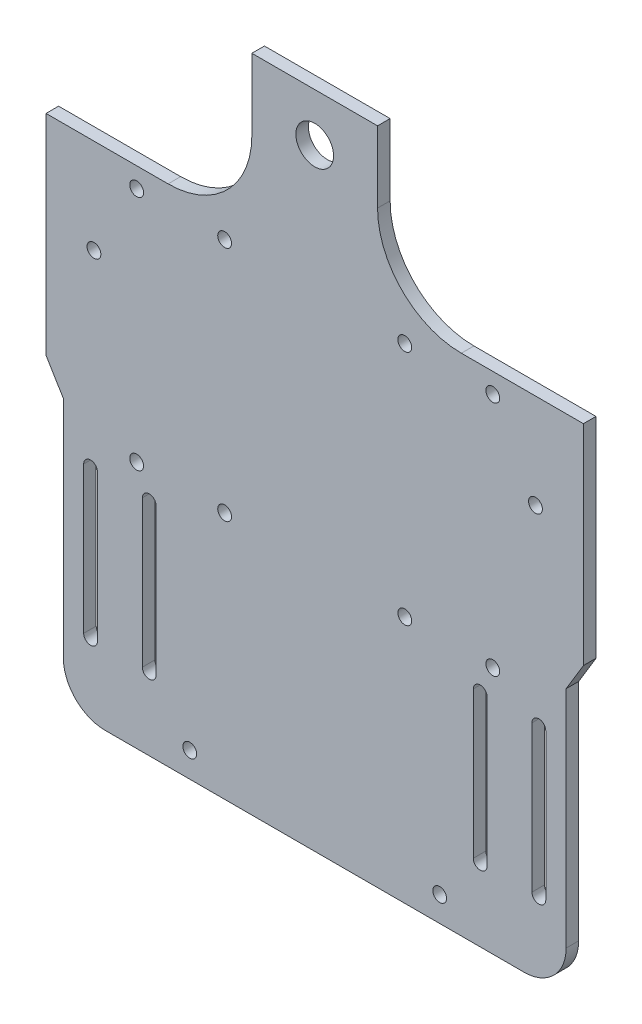
SolidWorks part; units mm, degrees
ref_plane "Front Plane" through (0, 0, 0) normal (0, 0, 1) x (1, 0, 0)
ref_plane "Top Plane" through (0, 0, 0) normal (0, 1, 0) x (1, 0, 0)
ref_plane "Right Plane" through (0, 0, 0) normal (1, 0, 0) x (0, 0, -1)
sketch "Sketch1" plane through (0, 0, 0) normal (0, 0, 1) x (1, 0, 0)
  line L0 (466.6281, 1797.6904) -> (466.6281, 1499.4405) construction
  line L7 (402.4958, 1683.2414) -> (402.4958, 1633.2414)
  line L8 (402.4958, 1633.2414) -> (406.6281, 1626.3913)
  line L14 (406.6281, 1562.7679) -> (526.6281, 1562.7679)
  line L20 (530.7604, 1633.2414) -> (526.6281, 1626.3913)
  line L21 (530.7604, 1683.2414) -> (530.7604, 1633.2414)
  line L25 (413.1281, 1615.2679) -> (413.1281, 1580.2679) construction
  line L26 (413.1281, 1615.2679) -> (413.1281, 1580.2679) construction
  line L27 (414.7781, 1615.2679) -> (414.7781, 1580.2679)
  line L28 (411.4781, 1615.2679) -> (411.4781, 1580.2679)
  line L30 (520.1281, 1615.2679) -> (520.1281, 1580.2679) construction
  line L31 (520.1281, 1615.2679) -> (520.1281, 1580.2679) construction
  line L32 (518.4781, 1615.2679) -> (518.4781, 1580.2679)
  line L33 (521.7781, 1615.2679) -> (521.7781, 1580.2679)
  line L35 (427.1281, 1615.2679) -> (427.1281, 1580.2679) construction
  line L36 (428.7781, 1615.2679) -> (428.7781, 1580.2679)
  line L37 (425.4781, 1615.2679) -> (425.4781, 1580.2679)
  line L38 (506.1281, 1615.2679) -> (506.1281, 1580.2679) construction
  line L39 (504.4781, 1615.2679) -> (504.4781, 1580.2679)
  line L40 (507.7781, 1615.2679) -> (507.7781, 1580.2679)
  line L49 (402.4958, 1683.2414) -> (451.6281, 1683.2414)
  line L53 (451.6281, 1683.2414) -> (451.6281, 1720.2414)
  line L54 (451.6281, 1720.2414) -> (481.6281, 1720.2414)
  line L55 (481.6281, 1683.2414) -> (481.6281, 1720.2414)
  line L56 (530.7604, 1683.2414) -> (481.6281, 1683.2414)
  line L57 (434.6281, 1697.6013) -> (434.6281, 1611.1356) construction
  line L58 (445.1281, 1610.6588) -> (445.1281, 1635.6152) construction
  line L59 (450.266, 1621.9914) -> (434.8467, 1621.9914) construction
  line L60 (418.9901, 1621.9914) -> (434.4095, 1621.9914) construction
  line L61 (424.1281, 1610.6588) -> (424.1281, 1635.6152) construction
  line L62 (418.9901, 1678.4914) -> (434.4095, 1678.4914) construction
  line L67 (450.266, 1678.4914) -> (434.8467, 1678.4914) construction
  line L68 (445.1281, 1689.8241) -> (445.1281, 1664.8676) construction
  line L69 (406.6281, 1626.3913) -> (406.6281, 1562.7679)
  line L70 (419.6949, 1708.7679) -> (502.9696, 1708.7679) construction
  line L71 (602.2349, 1683.2414) -> (337.9353, 1683.2414) construction
  line L72 (519.3209, 1708.8577) -> (519.3209, 1569.7658) construction
  line L73 (521.5101, 1660.6558) -> (543.6385, 1660.6558) construction
  line L86 (366.1855, 1650.2414) -> (561.5091, 1650.2414) construction
  line L91 (526.6281, 1626.3913) -> (526.6281, 1562.7679)
  line L92 (498.6281, 1697.6013) -> (498.6281, 1611.1356) construction
  line L93 (488.1281, 1689.8241) -> (488.1281, 1664.8676) construction
  line L96 (482.9901, 1678.4914) -> (498.4095, 1678.4914) construction
  line L99 (509.1281, 1689.8241) -> (509.1281, 1664.8676) construction
  line L100 (514.266, 1678.4914) -> (498.8467, 1678.4914) construction
  line L101 (388.1897, 1568.7679) -> (527.6187, 1568.7679) construction
  line L102 (488.1281, 1610.6588) -> (488.1281, 1635.6152) construction
  line L103 (482.9901, 1621.9914) -> (498.4095, 1621.9914) construction
  line L108 (514.266, 1621.9914) -> (498.8467, 1621.9914) construction
  line L109 (509.1281, 1610.6588) -> (509.1281, 1635.6152) construction
  line L114 (413.9353, 1708.8577) -> (413.9353, 1569.7658) construction
  line L115 (411.746, 1660.6558) -> (389.6176, 1660.6558) construction
  line L116 (424.1281, 1689.8241) -> (424.1281, 1664.8676) construction
  arc A0 (414.7781, 1615.2679) -> (411.4781, 1615.2679) centre (413.1281, 1615.2679) ccw
  arc A1 (411.4781, 1580.2679) -> (414.7781, 1580.2679) centre (413.1281, 1580.2679) ccw
  arc A2 (518.4781, 1615.2679) -> (521.7781, 1615.2679) centre (520.1281, 1615.2679) cw
  arc A3 (521.7781, 1580.2679) -> (518.4781, 1580.2679) centre (520.1281, 1580.2679) cw
  arc A4 (428.7781, 1615.2679) -> (425.4781, 1615.2679) centre (427.1281, 1615.2679) ccw
  arc A5 (425.4781, 1580.2679) -> (428.7781, 1580.2679) centre (427.1281, 1580.2679) ccw
  arc A6 (504.4781, 1615.2679) -> (507.7781, 1615.2679) centre (506.1281, 1615.2679) cw
  arc A7 (507.7781, 1580.2679) -> (504.4781, 1580.2679) centre (506.1281, 1580.2679) cw
  circle A12 centre (466.6281, 1708.7679) radius 4.5
  circle A13 centre (519.3209, 1660.6558) radius 1.65
  circle A20 centre (496.4498, 1568.7679) radius 1.65
  circle A24 centre (413.9353, 1660.6558) radius 1.65
  circle A26 centre (436.8064, 1568.7679) radius 1.65
  circle A31 centre (488.1281, 1678.4914) radius 1.65
  circle A32 centre (509.1281, 1678.4914) radius 1.65
  circle A33 centre (488.1281, 1621.9914) radius 1.65
  circle A34 centre (509.1281, 1621.9914) radius 1.65
  circle A35 centre (424.1281, 1621.9914) radius 1.65
  circle A36 centre (424.1281, 1678.4914) radius 1.65
  circle A37 centre (445.1281, 1678.4914) radius 1.65
  circle A38 centre (445.1281, 1621.9914) radius 1.65
  point P5 (466.6281, 1720.2414)
  point P17 (466.6281, 1562.7679)
  point P19 (520.1281, 1597.7679)
  point P29 (413.1281, 1597.7679)
  point P39 (427.1281, 1597.7679)
  point P46 (506.1281, 1597.7679)
  dimension "D12" = 3.3
  dimension "D20" = 29.8217
  dimension "D22" = 50
  dimension "D27" = 3.3
  dimension "D36" = 6
  dimension "D41" = 6
  dimension "D7" = 9
  dimension "D9" = 3.3
  dimension "D18" = 8
  dimension "D28" = 32
  dimension "D5" = 15
  dimension "D6" = 146
  dimension "D8" = 37
  dimension "D10" = 105.3856
  dimension "D11" = 120
  dimension "D13" = 14
  dimension "D14" = 3.3
  dimension "D15" = 128.2646
  dimension "D21" = 29.8217
  dimension "D23" = 35
  dimension "D24" = 35
  dimension "D25" = 35
  dimension "D26" = 35
  dimension "D29" = 10.5
  dimension "D30" = 28.25
  dimension "D31" = 33
  dimension "D37" = 59.6434
extrude "Boss-Extrude1" add sketch "Sketch1" along normal blind 3
fillet "Fillet3" radius 20 2 edges at (481.6281, 1683.2414, 1.5) (451.6281, 1683.2414, 1.5)
fillet "Fillet4" radius 10 2 edges at (526.6281, 1562.7679, 1.5) (406.6281, 1562.7679, 1.5)
